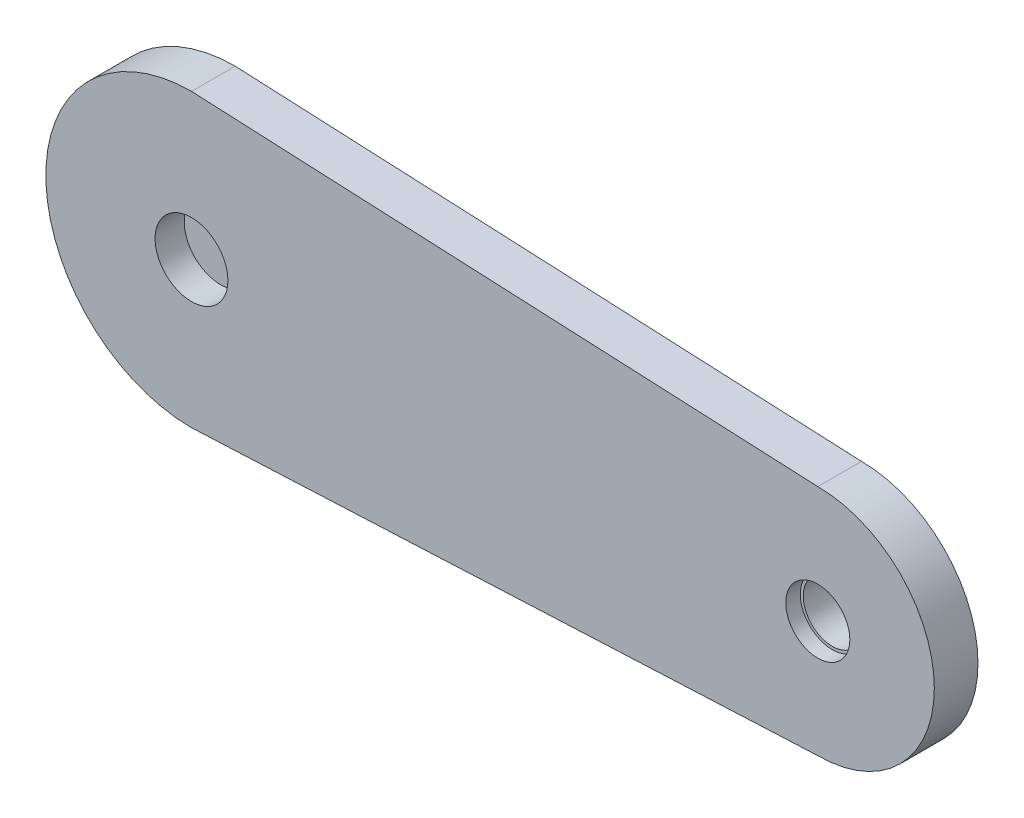
SolidWorks part; units mm, degrees
ref_plane "Alzado" through (0, 0, 0) normal (0, 0, 1) x (1, 0, 0)
ref_plane "Planta" through (0, 0, 0) normal (0, 1, 0) x (1, 0, 0)
ref_plane "Vista lateral" through (0, 0, 0) normal (1, 0, 0) x (0, 0, -1)
sketch "Croquis1" plane through (0, 0, 0) normal (0, 0, 1) x (1, 0, 0)
  line L0 (0, 0) -> (215, 0) construction
  line L1 (0, 50) -> (215, 40)
  line L2 (4.6411, -49.7841) -> (215, -40)
  arc A0 (0, 50) -> (4.6411, -49.7841) centre (0, 0) ccw
  arc A1 (215, -40) -> (215, 40) centre (215, 0) ccw
  circle A2 centre (0, 0) radius 1.25
  circle A3 centre (215, 0) radius 10
  dimension "D1" = 100
  dimension "D3" = 80
  dimension "D4" = 2.5
  dimension "D5" = 20
  dimension "D2" = 215
extrude "Saliente-Extruir1" add sketch "Croquis1" along normal blind 15
sketch "Croquis2" plane through (0, 0, 15) normal (0, 0, 1) x (1, 0, 0)
  circle A0 centre (0, 0) radius 12.5
  dimension "D1" = 25
extrude "Cortar-Extruir1" cut sketch "Croquis2" against normal blind 10
sketch "Croquis3" plane through (0, 0, 15) normal (0, 0, 1) x (1, 0, 0)
  circle A0 centre (215, 0) radius 11
  dimension "D1" = 22
extrude "Cortar-Extruir2" cut sketch "Croquis3" against normal blind 5
ref_plane "Plano1" through (0, 0, 0) normal (0, -1, 0) x (-1, 0, 0)
